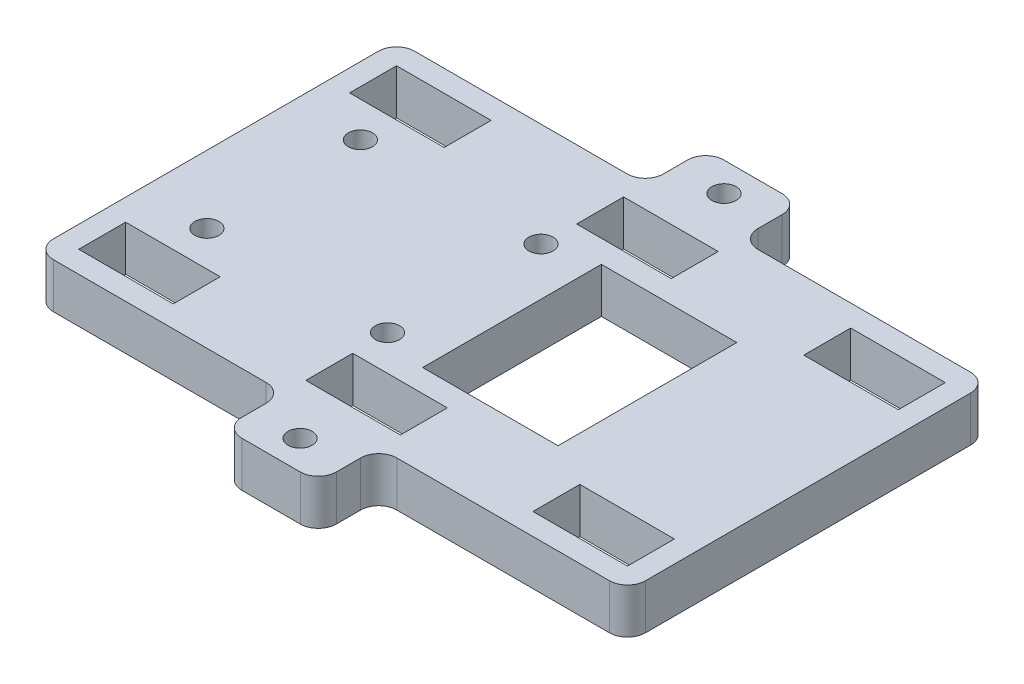
SolidWorks part; units mm, degrees
material "Acrylic (Medium-high impact)"
ref_plane "Front Plane" through (0, 0, 0) normal (0, 0, 1) x (1, 0, 0)
ref_plane "Top Plane" through (0, 0, 0) normal (0, 1, 0) x (1, 0, 0)
ref_plane "Right Plane" through (0, 0, 0) normal (1, 0, 0) x (0, 0, -1)
sketch "Sketch1" plane through (0, 0, 0) normal (0, 1, 0) x (1, 0, 0)
  line L0 (-25.2332, -25.4) -> (-6.5901, -25.4)
  line L1 (0.0612, -25.4) -> (0.0612, 25.4) construction
  line L2 (-41.5846, 25.4) -> (-41.5846, -25.4)
  line L3 (-32.0584, 10.795) -> (-6.6584, 10.795) construction
  line L4 (-32.0584, 10.795) -> (-32.0584, -10.795) construction
  line L5 (-32.0584, -10.795) -> (-6.6584, -10.795) construction
  line L6 (38.6582, 15.748) -> (38.6582, 22.225)
  line L7 (0.0612, 12.573) -> (19.1112, 12.573)
  line L8 (0.0612, 12.573) -> (0.0612, -12.573)
  line L9 (19.1112, 12.573) -> (19.1112, -12.573)
  line L10 (41.707, 25.4) -> (41.707, -25.4)
  line L11 (25.3557, 15.748) -> (25.3557, 22.352)
  line L12 (-41.5846, -25.4) -> (-38.5358, -25.4)
  line L13 (41.707, -25.4) -> (-41.5846, -25.4) construction
  line L14 (-38.5358, -25.4) -> (-38.5358, -33.8976) construction
  line L15 (41.707, 25.4) -> (-41.5846, 25.4) construction
  line L16 (-25.2332, 25.4) -> (0.0612, 25.4) construction
  line L17 (0.0612, 25.4) -> (25.3557, 25.4) construction
  line L18 (6.7125, -22.352) -> (-6.5901, -22.352)
  line L19 (-38.4088, 22.225) -> (-25.3602, 22.225) construction
  line L20 (-38.4088, 22.225) -> (-38.4088, 15.875) construction
  line L21 (-38.4088, 15.875) -> (-25.3602, 15.875) construction
  line L22 (-25.3602, 22.225) -> (-25.3602, 15.875) construction
  line L23 (6.7125, -22.352) -> (6.7125, -15.748)
  line L24 (6.7125, -15.748) -> (-6.5901, -15.748)
  line L25 (-6.5901, -22.352) -> (-6.5901, -15.748)
  line L26 (6.7125, -22.352) -> (-6.5901, -15.748) construction
  line L27 (25.4827, 22.225) -> (38.5312, 22.225) construction
  line L28 (25.4827, 22.225) -> (25.4827, 15.875) construction
  line L29 (25.4827, 15.875) -> (38.5312, 15.875) construction
  line L30 (38.5312, 22.225) -> (38.5312, 15.875) construction
  line L31 (6.7125, -15.748) -> (-6.5901, -22.352) construction
  line L32 (-6.5901, 15.748) -> (6.7125, 15.748)
  line L33 (38.5312, -22.225) -> (38.5312, -15.875) construction
  line L34 (25.4827, -15.875) -> (38.5312, -15.875) construction
  line L35 (25.4827, -22.225) -> (38.5312, -22.225) construction
  line L36 (25.4827, -22.225) -> (25.4827, -15.875) construction
  line L37 (-6.5901, 15.748) -> (-6.5901, 22.352)
  line L38 (-6.5901, 22.352) -> (6.7125, 22.352)
  line L39 (6.7125, 15.748) -> (6.7125, 22.352)
  line L40 (-6.5901, 15.748) -> (6.7125, 22.352) construction
  line L41 (-25.3602, -22.225) -> (-25.3602, -15.875) construction
  line L42 (-38.4088, -22.225) -> (-25.3602, -22.225) construction
  line L43 (-38.4088, -22.225) -> (-38.4088, -15.875) construction
  line L44 (-38.4088, -15.875) -> (-25.3602, -15.875) construction
  line L45 (-25.2332, -33.8976) -> (-25.2332, -25.4) construction
  line L46 (25.3557, -25.4) -> (25.3557, -33.8976) construction
  line L47 (-25.2332, -25.4) -> (25.3557, -25.4) construction
  line L48 (-6.5901, 22.352) -> (6.7125, 15.748) construction
  line L49 (41.707, -25.4) -> (38.6582, -25.4)
  line L50 (38.6582, -33.8976) -> (38.6582, -25.4) construction
  line L51 (-38.5358, 25.4) -> (-38.5358, 33.8976) construction
  line L52 (-38.5358, 33.8976) -> (-25.2332, 33.8976) construction
  line L53 (-25.2332, 33.8976) -> (-25.2332, 25.4) construction
  line L54 (-38.5358, 22.352) -> (-25.2332, 22.352)
  line L55 (-6.5901, -25.4) -> (-6.5901, -33.8976)
  line L56 (25.3557, 33.8976) -> (25.3557, 25.4) construction
  line L57 (25.3557, 15.748) -> (38.6582, 15.748)
  line L58 (-6.5901, -33.8976) -> (6.7125, -33.8976)
  line L59 (-38.5358, 22.352) -> (-38.5358, 15.748)
  line L60 (25.3557, 33.8976) -> (38.6582, 33.8976) construction
  line L61 (38.6582, 25.4) -> (38.6582, 33.8976) construction
  line L62 (25.3557, 22.352) -> (38.6582, 22.352)
  line L63 (25.3557, -33.8976) -> (38.6582, -33.8976) construction
  line L64 (-38.5358, 15.748) -> (-25.2332, 15.748)
  line L65 (-25.2332, 22.225) -> (-25.2332, 15.748)
  line L66 (-31.8845, 29.8145) -> (-31.8845, 33.8976) construction
  line L67 (32.0069, 29.8145) -> (32.0069, 33.8976) construction
  line L68 (6.7125, -33.8976) -> (6.7125, -25.4)
  line L69 (6.7125, -25.4) -> (25.3557, -25.4)
  line L70 (38.6582, 22.352) -> (38.6582, 22.225)
  line L71 (-25.2332, 22.352) -> (-25.2332, 22.225)
  line L72 (-38.5358, -33.8976) -> (-25.2332, -33.8976) construction
  line L73 (-25.2332, 25.4) -> (-6.5901, 25.4)
  line L74 (-38.5358, 25.4) -> (-25.2332, 25.4)
  line L75 (-6.5901, 25.4) -> (-6.5901, 33.8976)
  line L76 (-6.5901, 33.8976) -> (6.7125, 33.8976)
  line L77 (41.707, 25.4) -> (38.6582, 25.4)
  line L78 (6.7125, 25.4) -> (6.7125, 33.8976)
  line L79 (-38.5358, -22.352) -> (-38.5358, -15.748)
  line L80 (-38.5358, -15.748) -> (-25.2332, -15.748)
  line L81 (6.7125, 25.4) -> (25.3557, 25.4)
  line L82 (-25.2332, -22.352) -> (-25.2332, -15.748)
  line L83 (-38.5358, -22.352) -> (-25.2332, -22.352)
  line L84 (25.3557, 25.4) -> (38.6582, 25.4)
  line L85 (-41.5846, 25.4) -> (-38.5358, 25.4)
  line L86 (-38.5358, 22.225) -> (-38.5358, 15.748) construction
  line L87 (38.6582, -25.4) -> (25.3557, -25.4)
  line L88 (-25.2332, -25.4) -> (-38.5358, -25.4)
  line L90 (38.6582, -22.352) -> (38.6582, -15.748)
  line L91 (25.3557, -15.748) -> (38.6582, -15.748)
  line L92 (25.3557, -22.352) -> (25.3557, -15.748)
  line L93 (25.3557, -22.352) -> (38.6582, -22.352)
  line L94 (-31.8845, -33.8976) -> (-31.8845, -29.8145) construction
  line L95 (32.0069, -33.8976) -> (32.0069, -29.8145) construction
  line L96 (19.1112, -12.573) -> (0.0612, -12.573)
  line L97 (38.6582, 22.225) -> (38.6582, 15.748) construction
  line L98 (25.3557, 22.225) -> (25.3557, 15.748) construction
  circle A0 centre (-32.0584, 10.795) radius 1.7005
  circle A1 centre (-32.0584, -10.795) radius 1.7005
  circle A2 centre (-6.6584, -10.795) radius 1.7005
  circle A3 centre (-6.6584, 10.795) radius 1.7005
  circle A4 centre (-31.8845, -29.8145) radius 1.7005 construction
  circle A5 centre (32.0069, -29.8145) radius 1.7005 construction
  circle A6 centre (32.0069, 29.8145) radius 1.7005 construction
  circle A7 centre (-31.8845, 29.8145) radius 1.7005 construction
  circle A8 centre (0.0612, -29.8145) radius 1.7005
  circle A9 centre (0.0612, 29.8145) radius 1.7005
  point P0 (0.0612, -19.05)
  point P6 (0.0612, 0)
  point P11 (0.0612, 0)
  point P16 (-32.0584, 0)
  point P27 (0.0612, 19.05)
  dimension "D7" = 25.4
  dimension "D16" = 8.4976
  dimension "D17" = 12.573
  dimension "D23" = 3.4011
  dimension "D9" = 13.3026
  dimension "D3" = 83.2917
  dimension "D4" = 21.59
  dimension "D5" = 0.127
  dimension "D6" = 0.254
  dimension "D8" = 7.4625
  dimension "D10" = 3.0488
  dimension "D11" = 3.0488
  dimension "D12" = 0.127
  dimension "D13" = 3.048
  dimension "D14" = 19.05
  dimension "D15" = 10.795
  dimension "D18" = 15.875
  dimension "D19" = 22.352
  dimension "D20" = 25.4
  dimension "D21" = 0.127
  dimension "D22" = 13.3026
  dimension "D26" = 8.4976
extrude "Boss-Extrude1" add sketch "Sketch1" along normal blind 6.35
fillet "Fillet8" radius 2.54 12 edges at (41.707, 3.175, 25.4) (6.7125, 3.175, 25.4) (6.7125, 3.175, 33.8976) (-6.5901, 3.175, 33.8976) (-6.5901, 3.175, 25.4) (-41.5846, 3.175, 25.4) (41.707, 3.175, -25.4) (6.7125, 3.175, -25.4) (6.7125, 3.175, -33.8976) (-6.5901, 3.175, -33.8976) (-6.5901, 3.175, -25.4) (-41.5846, 3.175, -25.4)
equation "\"D10@Sketch1\"=\"D11@Sketch1\""
